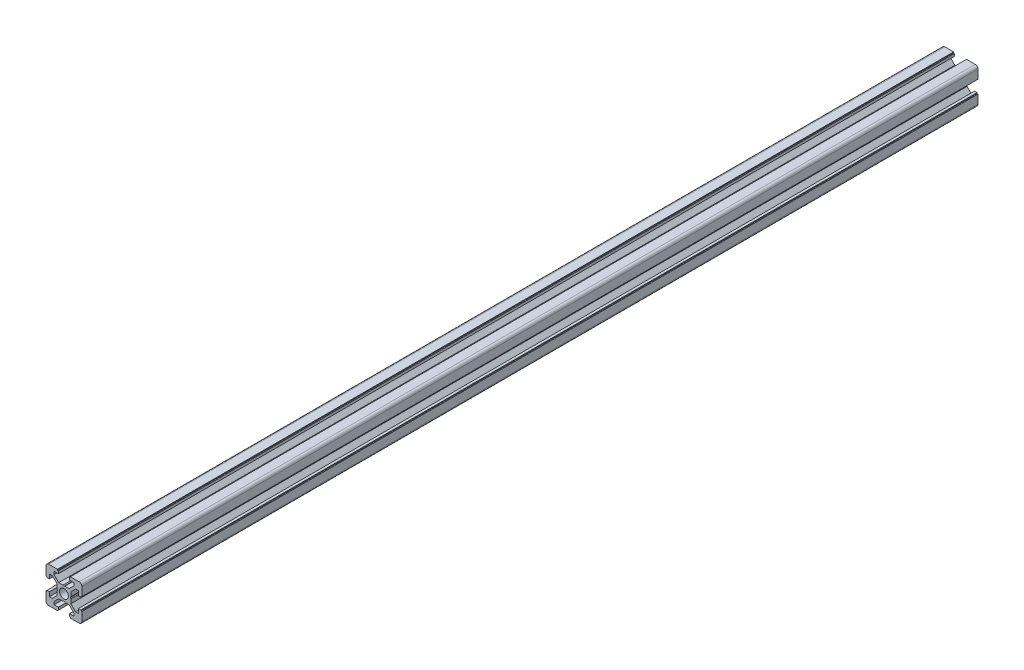
SolidWorks part; units mm, degrees
ref_plane "前视基准面" through (0, 0, 0) normal (0, 0, 1) x (1, 0, 0)
ref_plane "上视基准面" through (0, 0, 0) normal (0, 1, 0) x (1, 0, 0)
ref_plane "右视基准面" through (0, 0, 0) normal (1, 0, 0) x (0, 0, -1)
sketch "草图28" plane through (0, 0, 0) normal (0, 0, 1) x (1, 0, 0)
  line B0 (0, 11.0182) -> (0, -11.0182) construction
  line B1 (-11.0182, 0) -> (11.0182, 0) construction
  line B2 (-3.9, -0.5196) -> (-3.9, -2.9101)
  line B3 (-3.9, -2.9101) -> (-6.4899, -5.5)
  line B4 (-6.4899, -5.5) -> (-8.1, -5.5)
  line B5 (-8.1, -5.5) -> (-8.1, -3.1)
  line B6 (-8.1, -3.1) -> (-9.5, -3.1)
  line B7 (-9.5, -3.1) -> (-9.5, -3.6)
  line B8 (-9.5, -3.6) -> (-10, -3.6)
  line B9 (-10, -3.6) -> (-10, -8.5)
  line B10 (-8.5, -10) -> (-3.6, -10)
  line B11 (-3.6, -10) -> (-3.6, -9.5)
  line B12 (-3.6, -9.5) -> (-3.1, -9.5)
  line B13 (-3.1, -9.5) -> (-3.1, -8.1)
  line B14 (-3.1, -8.1) -> (-5.5, -8.1)
  line B15 (-5.5, -8.1) -> (-5.5, -6.4899)
  line B16 (-5.5, -6.4899) -> (-2.9101, -3.9)
  line B17 (-2.9101, -3.9) -> (-0.5196, -3.9)
  line B18 (-0.5196, -3.9) -> (0, -3.6)
  line B19 (0, -3.6) -> (0.5196, -3.9)
  line B20 (0.5196, -3.9) -> (2.9101, -3.9)
  line B21 (2.9101, -3.9) -> (5.5, -6.4899)
  line B22 (5.5, -6.4899) -> (5.5, -8.1)
  line B23 (5.5, -8.1) -> (3.1, -8.1)
  line B24 (3.1, -8.1) -> (3.1, -9.5)
  line B25 (3.1, -9.5) -> (3.6, -9.5)
  line B26 (3.6, -9.5) -> (3.6, -10)
  line B27 (3.6, -10) -> (8.5, -10)
  line B28 (10, -8.5) -> (10, -3.6)
  line B29 (10, -3.6) -> (9.5, -3.6)
  line B30 (9.5, -3.6) -> (9.5, -3.1)
  line B31 (9.5, -3.1) -> (8.1, -3.1)
  line B32 (8.1, -3.1) -> (8.1, -5.5)
  line B33 (8.1, -5.5) -> (6.4899, -5.5)
  line B34 (6.4899, -5.5) -> (3.9, -2.9101)
  line B35 (3.9, -2.9101) -> (3.9, -0.5196)
  line B36 (3.9, -0.5196) -> (3.6, 0)
  line B37 (3.6, 0) -> (3.9, 0.5196)
  line B38 (3.9, 0.5196) -> (3.9, 2.9101)
  line B39 (3.9, 2.9101) -> (6.4899, 5.5)
  line B40 (6.4899, 5.5) -> (8.1, 5.5)
  line B41 (8.1, 5.5) -> (8.1, 3.1)
  line B42 (8.1, 3.1) -> (9.5, 3.1)
  line B43 (9.5, 3.1) -> (9.5, 3.6)
  line B44 (9.5, 3.6) -> (10, 3.6)
  line B45 (10, 3.6) -> (10, 8.5)
  line B46 (8.5, 10) -> (3.6, 10)
  line B47 (3.6, 10) -> (3.6, 9.5)
  line B48 (3.6, 9.5) -> (3.1, 9.5)
  line B49 (3.1, 9.5) -> (3.1, 8.1)
  line B50 (3.1, 8.1) -> (5.5, 8.1)
  line B51 (5.5, 8.1) -> (5.5, 6.4899)
  line B52 (5.5, 6.4899) -> (2.9101, 3.9)
  line B53 (2.9101, 3.9) -> (0.5196, 3.9)
  line B54 (0.5196, 3.9) -> (0, 3.6)
  line B55 (0, 3.6) -> (-0.5196, 3.9)
  line B56 (-0.5196, 3.9) -> (-2.9101, 3.9)
  line B57 (-2.9101, 3.9) -> (-5.5, 6.4899)
  line B58 (-5.5, 6.4899) -> (-5.5, 8.1)
  line B59 (-5.5, 8.1) -> (-3.1, 8.1)
  line B60 (-3.1, 8.1) -> (-3.1, 9.5)
  line B61 (-3.1, 9.5) -> (-3.6, 9.5)
  line B62 (-3.6, 9.5) -> (-3.6, 10)
  line B63 (-3.6, 10) -> (-8.5, 10)
  line B64 (-10, 8.5) -> (-10, 3.6)
  line B65 (-10, 3.6) -> (-9.5, 3.6)
  line B66 (-9.5, 3.6) -> (-9.5, 3.1)
  line B67 (-9.5, 3.1) -> (-8.1, 3.1)
  line B68 (-8.1, 3.1) -> (-8.1, 5.5)
  line B69 (-8.1, 5.5) -> (-6.4899, 5.5)
  line B70 (-6.4899, 5.5) -> (-3.9, 2.9101)
  line B71 (-3.9, 2.9101) -> (-3.9, 0.5196)
  line B72 (-3.9, 0.5196) -> (-3.6, 0)
  line B73 (-3.6, 0) -> (-3.9, -0.5196)
  circle B74 centre (0, 0) radius 2.5
  arc B75 (-10, -8.5) -> (-8.5, -10) centre (-8.5, -8.5) ccw
  arc B76 (8.5, -10) -> (10, -8.5) centre (8.5, -8.5) ccw
  arc B77 (10, 8.5) -> (8.5, 10) centre (8.5, 8.5) ccw
  arc B78 (-8.5, 10) -> (-10, 8.5) centre (-8.5, 8.5) ccw
sketch_block_instance "块1-1"
sketch_block "块1"
extrude "凸台-拉伸1" add sketch "草图28" along normal blind 500
cosmetic thread "装饰螺纹线1" [suppressed] parameters "D1"=15, "D2"=6
cosmetic thread "装饰螺纹线2" [suppressed] parameters "D1"=15, "D2"=6
ref_plane "基准面1" through (0, 0, 500) normal (0, 0, 1) x (1, 0, 0)
ref_plane "基准面2" through (0, 10, 0) normal (0, 1, 0) x (1, 0, 0)
ref_plane "基准面3" through (0, -10, 0) normal (0, 1, 0) x (1, 0, 0)
ref_plane "基准面4" through (10, 0, 0) normal (1, 0, 0) x (0, 0, -1)
ref_plane "基准面5" through (-10, 0, 0) normal (1, 0, 0) x (0, 0, -1)
sketch "草图19" plane through (0, 0, 0) normal (0, 0, 1) x (1, 0, 0)
  line L0 (0, 0) -> (0, 11.6901) construction
  line L1 (0, 0) -> (10.3437, 0) construction
sketch "草图20" plane through (0, 0, 0) normal (0, 1, 0) x (1, 0, 0)
  line L0 (0, 0) -> (0, 3.5576) construction
ref_point "点1"
sketch "草图2" [suppressed] plane through (0, 0, 0) normal (1, 0, 0) x (0, 0, -1)
  line L0 (-280, -10) -> (-260, 10)
  line L1 (11, -10) -> (-11, -10) construction
  line L2 (11, 10) -> (-11, 10) construction
  line L3 (-260, 10) -> (-280, 10)
  line L4 (-280, 11) -> (-280, -11) construction
  line L5 (-280, 10) -> (-280, -10)
  dimension "D1" = 45
extrude "切除-拉伸1" [suppressed] cut sketch "草图2" against normal through all and the other way through all
sketch "草图3" [suppressed] plane through (0, 0, 0) normal (1, 0, 0) x (0, 0, -1)
  line L0 (0, -10) -> (-20, 10)
  line L1 (11, -10) -> (-11, -10) construction
  line L2 (11, 10) -> (-11, 10) construction
  line L3 (-20, 10) -> (0, 10)
  line L4 (0, 10) -> (0, -10)
  line L5 (0, 11) -> (0, -11) construction
  dimension "D1" = 45
extrude "切除-拉伸2" [suppressed] cut sketch "草图3" against normal through all and the other way through all
sketch "草图4" [suppressed] plane through (0, 0, 0) normal (1, 0, 0) x (0, 0, -1)
  line L0 (-280, 10) -> (-260, -10)
  line L1 (11, 10) -> (-11, 10) construction
  line L2 (-280, 11) -> (-280, -11) construction
  line L3 (11, -10) -> (-11, -10) construction
  line L4 (-260, -10) -> (-280, -10)
  line L5 (-280, -10) -> (-280, 10)
  dimension "D1" = 45
extrude "切除-拉伸3" [suppressed] cut sketch "草图4" against normal through all and the other way through all
sketch "草图5" [suppressed] plane through (0, 0, 0) normal (1, 0, 0) x (0, 0, -1)
  line L0 (0, 10) -> (-20, -10)
  line L1 (11, 10) -> (-11, 10) construction
  line L2 (11, -10) -> (-11, -10) construction
  line L3 (-20, -10) -> (0, -10)
  line L4 (0, -10) -> (0, 10)
  line L5 (0, 11) -> (0, -11) construction
  dimension "D1" = 45
extrude "切除-拉伸4" [suppressed] cut sketch "草图5" against normal through all and the other way through all
sketch "草图6" [suppressed] plane through (0, 0, 0) normal (0, 1, 0) x (1, 0, 0)
  line L0 (-10, -280) -> (10, -260)
  line L1 (-10, -11) -> (-10, 11) construction
  line L2 (-11, -280) -> (11, -280) construction
  line L3 (10, -11) -> (10, 11) construction
  line L4 (10, -260) -> (10, -280)
  line L5 (10, -280) -> (-10, -280)
  dimension "D1" = 45
extrude "切除-拉伸5" [suppressed] cut sketch "草图6" against normal through all and the other way through all
sketch "草图7" [suppressed] plane through (0, 0, 0) normal (0, 1, 0) x (1, 0, 0)
  line L0 (-10, 0) -> (10, -20)
  line L1 (-10, -11) -> (-10, 11) construction
  line L2 (10, -11) -> (10, 11) construction
  line L3 (10, -20) -> (10, 0)
  line L4 (-11, 0) -> (11, 0) construction
  line L5 (10, 0) -> (-10, 0)
  dimension "D1" = 45
extrude "切除-拉伸6" [suppressed] cut sketch "草图7" against normal through all and the other way through all
sketch "草图8" [suppressed] plane through (0, 0, 0) normal (0, 1, 0) x (1, 0, 0)
  line L0 (-10, -260) -> (10, -280)
  line L1 (-10, -11) -> (-10, 11) construction
  line L2 (10, -11) -> (10, 11) construction
  line L3 (-11, -280) -> (11, -280) construction
  line L4 (10, -280) -> (-10, -280)
  line L5 (-10, -280) -> (-10, -260)
  dimension "D1" = 45
extrude "切除-拉伸7" [suppressed] cut sketch "草图8" against normal through all and the other way through all
sketch "草图9" [suppressed] plane through (0, 0, 0) normal (0, 1, 0) x (1, 0, 0)
  line L0 (10, 0) -> (-10, -20)
  line L1 (10, -11) -> (10, 11) construction
  line L2 (-11, 0) -> (11, 0) construction
  line L3 (-10, -11) -> (-10, 11) construction
  line L4 (-10, -20) -> (-10, 0)
  line L5 (-10, 0) -> (10, 0)
  dimension "D1" = 45
extrude "切除-拉伸8" [suppressed] cut sketch "草图9" against normal through all and the other way through all
sketch "草图10" [suppressed] plane through (10, -3.64, 139.7) normal (1, 0, 0) x (0, 0, -1)
  line L1 (-140.3, 14.64) -> (-140.3, -7.36) construction
  circle A0 centre (-127.3, 3.64) radius 6.25
  dimension "D1" = 12.5
  dimension "D2" = 13
extrude "切除-拉伸9" [suppressed] cut sketch "草图10" against normal blind 9
sketch "草图11" [suppressed] plane through (10, 0, 0) normal (1, 0, 0) x (0, 0, -1)
  circle A0 centre (-13, 0) radius 6.25
  dimension "D1" = 12.5
  dimension "D2" = 13
extrude "切除-拉伸10" [suppressed] cut sketch "草图11" against normal blind 9
sketch "草图12" [suppressed] plane through (0, 0, 0) normal (0, 1, 0) x (1, 0, 0)
  line L0 (-10, -11) -> (-10, 11) construction
  line L1 (-10, -267) -> (-1, -267)
  line L2 (-10, -267) -> (-10, -260.75)
  line L3 (-10, -260.75) -> (-1, -260.75)
  line L4 (-1, -267) -> (-1, -260.75)
  line L5 (10, -11) -> (10, 11) construction
  line L6 (10, -267) -> (1, -267)
  line L7 (10, -267) -> (10, -260.75)
  line L8 (10, -260.75) -> (1, -260.75)
  line L9 (1, -267) -> (1, -260.75)
  line L10 (-11, -280) -> (11, -280) construction
  dimension "D1" = 13
  dimension "D2" = 6.25
  dimension "D3" = 9
revolve "切除-旋转1" [suppressed] cut sketch "草图12" angle 360 about L1
sketch "草图13" [suppressed] plane through (0, 0, 0) normal (0, 1, 0) x (1, 0, 0)
  line L0 (-10, -11) -> (-10, 11) construction
  line L1 (-10, -19.25) -> (-1, -19.25)
  line L2 (-10, -19.25) -> (-10, -13)
  line L3 (-10, -13) -> (-1, -13)
  line L4 (-1, -19.25) -> (-1, -13)
  line L5 (10, -11) -> (10, 11) construction
  line L6 (10, -19.25) -> (1, -19.25)
  line L7 (10, -19.25) -> (10, -13)
  line L8 (10, -13) -> (1, -13)
  line L9 (1, -19.25) -> (1, -13)
  dimension "D1" = 13
  dimension "D2" = 6.25
  dimension "D3" = 9
revolve "切除-旋转2" [suppressed] cut sketch "草图13" angle 360 about L3
sketch "草图14" [suppressed] plane through (0, 10, 0) normal (0, 1, 0) x (1, 0, 0)
  line L0 (-11, -280) -> (11, -280) construction
  circle A0 centre (0, -267) radius 6.25
  dimension "D1" = 12.5
  dimension "D2" = 13
extrude "切除-拉伸11" [suppressed] cut sketch "草图14" against normal blind 9
sketch "草图15" [suppressed] plane through (0, 10, 0) normal (0, 1, 0) x (1, 0, 0)
  line L0 (-11, 0) -> (11, 0) construction
  circle A0 centre (0, -13) radius 6.25
  dimension "D1" = 12.5
  dimension "D2" = 13
extrude "切除-拉伸12" [suppressed] cut sketch "草图15" against normal blind 9
sketch "草图16" [suppressed] plane through (0, 0, 0) normal (1, 0, 0) x (0, 0, -1)
  line L0 (11, 10) -> (-11, 10) construction
  line L1 (-267, 10) -> (-260.75, 10)
  line L2 (-267, 10) -> (-267, 1)
  line L3 (-267, 1) -> (-260.75, 1)
  line L4 (-260.75, 10) -> (-260.75, 1)
  line L5 (11, -10) -> (-11, -10) construction
  line L6 (-267, -10) -> (-260.75, -10)
  line L7 (-267, -10) -> (-267, -1)
  line L8 (-267, -1) -> (-260.75, -1)
  line L9 (-260.75, -10) -> (-260.75, -1)
  line L10 (-280, 11) -> (-280, -11) construction
  dimension "D1" = 9
  dimension "D2" = 6.25
  dimension "D3" = 13
revolve "切除-旋转3" [suppressed] cut sketch "草图16" angle 360 about L2
sketch "草图17" [suppressed] plane through (0, 0, 0) normal (1, 0, 0) x (0, 0, -1)
  line L0 (11, 10) -> (-11, 10) construction
  line L1 (-13, 10) -> (-19.25, 10)
  line L2 (-13, 10) -> (-13, 1)
  line L3 (-13, 1) -> (-19.25, 1)
  line L4 (-19.25, 10) -> (-19.25, 1)
  line L5 (11, -10) -> (-11, -10) construction
  line L6 (-13, -10) -> (-19.25, -10)
  line L7 (-13, -10) -> (-13, -1)
  line L8 (-13, -1) -> (-19.25, -1)
  line L9 (-19.25, -10) -> (-19.25, -1)
  dimension "D1" = 6.25
  dimension "D2" = 9
  dimension "D3" = 13
revolve "切除-旋转4" [suppressed] cut sketch "草图17" angle 360 about L2
sketch "草图18" [suppressed] plane through (0, 0, 0) normal (0, 1, 0) x (1, 0, 0)
  line L0 (-10, -230) -> (10, -230)
  line L1 (-10, -11) -> (-10, 11) construction
  line L2 (10, -11) -> (10, 11) construction
  line L3 (10, -230) -> (10, -224.5)
  line L4 (10, -224.5) -> (3.5, -224.5)
  line L5 (3.5, -224.5) -> (3.5, -226.75)
  line L6 (3.5, -226.75) -> (-10, -226.75)
  line L7 (-10, -226.75) -> (-10, -230)
  line L8 (-11, -280) -> (11, -280) construction
  dimension "D1" = 50
  dimension "D2" = 5.5
  dimension "D3" = 3.25
  dimension "D4" = 6.5
revolve "切除-旋转5" [suppressed] cut sketch "草图18" angle 360 about L0
other "表格阵列1" [suppressed] parameters "D0"=70, "D1"=0, "D2"=90, "D3"=0, "D4"=110, "D5"=0, "D6"=130, "D7"=0
sketch "草图21" [suppressed] plane through (0, 0, 0) normal (0, 1, 0) x (1, 0, 0)
  line L0 (-10, -50) -> (10, -50)
  line L1 (-10, -11) -> (-10, 11) construction
  line L2 (10, -11) -> (10, 11) construction
  line L3 (10, -50) -> (10, -55.5)
  line L4 (10, -55.5) -> (3.5, -55.5)
  line L5 (3.5, -55.5) -> (3.5, -53.25)
  line L6 (3.5, -53.25) -> (-10, -53.25)
  line L7 (-10, -53.25) -> (-10, -50)
  dimension "D1" = 5.5
  dimension "D2" = 3.25
  dimension "D3" = 6.5
  dimension "D4" = 50
revolve "切除-旋转6" [suppressed] cut sketch "草图21" angle 360 about L0
other "表格阵列2" [suppressed] parameters "D0"=70, "D1"=0, "D2"=90, "D3"=0, "D4"=110, "D5"=0, "D6"=130, "D7"=0
sketch "草图22" [suppressed] plane through (0, 0, 0) normal (1, 0, 0) x (0, 0, -1)
  line L0 (-230, 10) -> (-230, -10)
  line L1 (11, 10) -> (-11, 10) construction
  line L2 (11, -10) -> (-11, -10) construction
  line L3 (-230, -10) -> (-226.75, -10)
  line L4 (-226.75, -10) -> (-226.75, 3.5)
  line L5 (-226.75, 3.5) -> (-224.5, 3.5)
  line L6 (-224.5, 3.5) -> (-224.5, 10)
  line L7 (-224.5, 10) -> (-230, 10)
  line L8 (-280, 11) -> (-280, -11) construction
  dimension "D1" = 5.5
  dimension "D2" = 3.25
  dimension "D3" = 6.5
  dimension "D4" = 50
revolve "切除-旋转7" [suppressed] cut sketch "草图22" angle 360 about L0
other "表格阵列3" [suppressed] parameters "D0"=70, "D1"=0, "D2"=90, "D3"=0, "D4"=110, "D5"=0, "D6"=130, "D7"=0
sketch "草图23" [suppressed] plane through (0, 0, 0) normal (1, 0, 0) x (0, 0, -1)
  line L0 (-50, 10) -> (-55.5, 10)
  line L1 (11, 10) -> (-11, 10) construction
  line L2 (-55.5, 10) -> (-55.5, 3.5)
  line L3 (-55.5, 3.5) -> (-53.25, 3.5)
  line L4 (-53.25, 3.5) -> (-53.25, -10)
  line L5 (11, -10) -> (-11, -10) construction
  line L6 (-53.25, -10) -> (-50, -10)
  line L7 (-50, -10) -> (-50, 10)
  dimension "D1" = 5.5
  dimension "D2" = 3.25
  dimension "D3" = 6.5
  dimension "D4" = 50
revolve "切除-旋转8" [suppressed] cut sketch "草图23" angle 360 about L7
other "表格阵列4" [suppressed] parameters "D0"=70, "D1"=0, "D2"=90, "D3"=0, "D4"=110, "D5"=0, "D6"=130, "D7"=0
sketch "草图24" [suppressed] plane through (10, 0, 0) normal (1, 0, 0) x (0, 0, -1)
  line L0 (-280, 11) -> (-280, -11) construction
  circle A0 centre (-240, 0) radius 3.25
  dimension "D1" = 6.5
  dimension "D2" = 40
extrude "切除-拉伸13" [suppressed] cut sketch "草图24" against normal through all
other "表格阵列5" [suppressed] parameters "D0"=60, "D1"=0, "D2"=80, "D3"=0, "D4"=100, "D5"=0, "D6"=120, "D7"=0
sketch "草图25" [suppressed] plane through (10, 0, 0) normal (1, 0, 0) x (0, 0, -1)
  circle A0 centre (-40, 0) radius 3.25
  dimension "D1" = 6.5
  dimension "D2" = 40
extrude "切除-拉伸14" [suppressed] cut sketch "草图25" against normal through all
other "表格阵列6" [suppressed] parameters "D0"=60, "D1"=0, "D2"=80, "D3"=0, "D4"=100, "D5"=0, "D6"=120, "D7"=0
sketch "草图26" [suppressed] plane through (0, 10, 0) normal (0, 1, 0) x (1, 0, 0)
  line L0 (-11, -280) -> (11, -280) construction
  circle A0 centre (0, -240) radius 3.25
  dimension "D1" = 6.5
  dimension "D2" = 40
extrude "切除-拉伸15" [suppressed] cut sketch "草图26" against normal through all
other "表格阵列7" [suppressed] parameters "D0"=60, "D1"=0, "D2"=80, "D3"=0, "D4"=100, "D5"=0, "D6"=120, "D7"=0
sketch "草图27" [suppressed] plane through (0, 10, 0) normal (0, 1, 0) x (1, 0, 0)
  circle A0 centre (0, -40) radius 3.25
  dimension "D1" = 6.5
  dimension "D2" = 40
extrude "切除-拉伸16" [suppressed] cut sketch "草图27" against normal through all
other "表格阵列8" [suppressed] parameters "D0"=60, "D1"=0, "D2"=80, "D3"=0, "D4"=100, "D5"=0, "D6"=120, "D7"=0
sketch "草图29" [suppressed] plane through (0, 0, 0) normal (0, 1, 0) x (1, 0, 0)
  line L0 (-10, -230) -> (-10, -224.5)
  line L1 (-10, -224.5) -> (-3.5, -224.5)
  line L2 (-3.5, -224.5) -> (-3.5, -226.75)
  line L3 (-3.5, -226.75) -> (10, -226.75)
  line L4 (10, -226.75) -> (10, -230)
  line L5 (10, -230) -> (-10, -230)
  line L6 (-10, -11) -> (-10, 11) construction
  line L7 (10, -11) -> (10, 11) construction
  line L8 (-11, -280) -> (11, -280) construction
  dimension "D1" = 3.25
  dimension "D2" = 5.5
  dimension "D3" = 6.5
  dimension "D4" = 50
revolve "切除-旋转9" [suppressed] cut sketch "草图29" angle 360 about L5
other "表格阵列9" [suppressed] parameters "D0"=70, "D1"=0, "D2"=90, "D3"=0, "D4"=110, "D5"=0, "D6"=130, "D7"=0
sketch "草图30" [suppressed] plane through (0, 0, 0) normal (0, 1, 0) x (1, 0, 0)
  line L0 (10, -50) -> (10, -53.25)
  line L1 (10, -53.25) -> (-3.5, -53.25)
  line L2 (-3.5, -53.25) -> (-3.5, -55.5)
  line L3 (-3.5, -55.5) -> (-10, -55.5)
  line L4 (-10, -55.5) -> (-10, -50)
  line L5 (-10, -50) -> (10, -50)
  line L6 (-10, -11) -> (-10, 11) construction
  line L7 (10, -11) -> (10, 11) construction
  dimension "D1" = 5.5
  dimension "D2" = 6.5
  dimension "D3" = 3.25
  dimension "D4" = 50
revolve "切除-旋转10" [suppressed] cut sketch "草图30" angle 360 about L5
other "表格阵列10" [suppressed] parameters "D0"=70, "D1"=0, "D2"=90, "D3"=0, "D4"=110, "D5"=0, "D6"=130, "D7"=0
sketch "草图31" [suppressed] plane through (0, 0, 0) normal (1, 0, 0) x (0, 0, -1)
  line L0 (-230, 10) -> (-226.75, 10)
  line L1 (-226.75, 10) -> (-226.75, -3.5)
  line L2 (-226.75, -3.5) -> (-224.5, -3.5)
  line L3 (-224.5, -3.5) -> (-224.5, -10)
  line L4 (-224.5, -10) -> (-230, -10)
  line L5 (-230, -10) -> (-230, 10)
  line L6 (11, 10) -> (-11, 10) construction
  line L7 (11, -10) -> (-11, -10) construction
  line L8 (-280, 11) -> (-280, -11) construction
  dimension "D1" = 3.25
  dimension "D2" = 5.5
  dimension "D3" = 6.5
  dimension "D4" = 50
revolve "切除-旋转11" [suppressed] cut sketch "草图31" angle 360 about L5
other "表格阵列11" [suppressed] parameters "D0"=70, "D1"=0, "D2"=90, "D3"=0, "D4"=110, "D5"=0, "D6"=130, "D7"=0
sketch "草图32" [suppressed] plane through (0, 0, 0) normal (1, 0, 0) x (0, 0, -1)
  line L0 (-50, 10) -> (-53.25, 10)
  line L1 (-53.25, 10) -> (-53.25, -3.5)
  line L2 (-53.25, -3.5) -> (-55.5, -3.5)
  line L3 (-55.5, -3.5) -> (-55.5, -10)
  line L4 (-55.5, -10) -> (-50, -10)
  line L5 (-50, -10) -> (-50, 10)
  line L6 (11, 10) -> (-11, 10) construction
  line L7 (11, -10) -> (-11, -10) construction
  dimension "D1" = 3.25
  dimension "D2" = 5.5
  dimension "D3" = 6.5
  dimension "D4" = 50
revolve "切除-旋转12" [suppressed] cut sketch "草图32" angle 360 about L5
other "表格阵列12" [suppressed] parameters "D0"=70, "D1"=0, "D2"=90, "D3"=0, "D4"=110, "D5"=0, "D6"=130, "D7"=0
